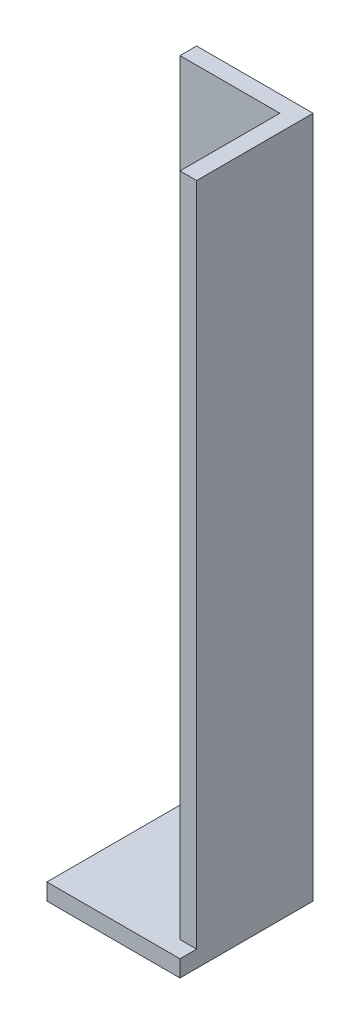
SolidWorks part; units mm, degrees
ref_plane "前视基准面" through (0, 0, 0) normal (0, 0, 1) x (1, 0, 0)
ref_plane "上视基准面" through (0, 0, 0) normal (0, 1, 0) x (1, 0, 0)
ref_plane "右视基准面" through (0, 0, 0) normal (1, 0, 0) x (0, 0, -1)
sketch "草图1" plane through (0, 0, 0) normal (0, 1, 0) x (1, 0, 0)
  line L0 (-38.6765, 43.0123) -> (-38.6765, -56.9877)
  line L1 (-38.6765, -56.9877) -> (61.3235, -56.9877)
  line L2 (61.3235, -56.9877) -> (61.3235, 43.0123)
  line L3 (61.3235, 43.0123) -> (-38.6765, 43.0123)
  dimension "D1" = 100
  dimension "D2" = 100
extrude "凸台-拉伸1" add sketch "草图1" along normal blind 10
sketch "草图2" plane through (0, 10, 0) normal (0, 1, 0) x (1, 0, 0)
  line L4 (61.3235, 43.0123) -> (-38.6765, 43.0123)
  line L5 (-38.6765, 43.0123) -> (-38.6765, -56.9877)
  line L6 (-38.6765, -56.9877) -> (61.3235, -56.9877)
  line L7 (61.3235, -56.9877) -> (61.3235, 43.0123)
  line L8 (61.3235, 43.0123) -> (-38.6765, 43.0123) construction
  line L9 (-38.6765, 43.0123) -> (-38.6765, -56.9877) construction
  line L10 (-38.6765, -56.9877) -> (61.3235, -56.9877) construction
  line L11 (61.3235, -56.9877) -> (61.3235, 43.0123) construction
  line L16 (51.3235, 33.0123) -> (-28.6765, 33.0123)
  line L17 (-28.6765, 33.0123) -> (-28.6765, -46.9877)
  line L18 (-28.6765, -46.9877) -> (51.3235, -46.9877)
  line L19 (51.3235, -46.9877) -> (51.3235, 33.0123)
  line L20 (51.3235, 33.0123) -> (-18.6765, 33.0123)
  line L21 (-28.6765, 33.0123) -> (-28.6765, -46.9877) construction
  line L22 (-28.6765, -46.9877) -> (51.3235, -46.9877) construction
  line L23 (51.3235, -36.9877) -> (51.3235, 33.0123)
  line L24 (-18.6765, 23.0123) -> (-18.6765, 33.0123)
  line L25 (41.3235, -36.9877) -> (51.3235, -36.9877)
  line L28 (41.3235, 23.0123) -> (-18.6765, 23.0123)
  line L29 (-18.6765, 23.0123) -> (-18.6765, -36.9877)
  line L30 (-18.6765, -36.9877) -> (41.3235, -36.9877)
  line L31 (41.3235, -36.9877) -> (41.3235, 23.0123)
  line L32 (41.3235, 23.0123) -> (-18.6765, 23.0123)
  line L33 (-18.6765, 23.0123) -> (-18.6765, -36.9877) construction
  line L34 (-18.6765, -36.9877) -> (41.3235, -36.9877) construction
  line L35 (41.3235, -36.9877) -> (41.3235, 23.0123)
  dimension "D1" = 0
  dimension "D2" = 10
  dimension "D3" = 20
extrude "凸台-拉伸2" add sketch "草图2" along normal blind 400
sketch "草图3" plane through (0, 10, 0) normal (0, 1, 0) x (1, 0, 0)
  line L8 (51.3235, 33.0123) -> (-28.6765, 33.0123)
  line L9 (-28.6765, 33.0123) -> (-28.6765, -46.9877)
  line L10 (-28.6765, -46.9877) -> (51.3235, -46.9877)
  line L11 (51.3235, -46.9877) -> (51.3235, 33.0123)
  line L12 (51.3235, 33.0123) -> (-28.6765, 33.0123)
  line L13 (-28.6765, 33.0123) -> (-28.6765, -46.9877)
  line L14 (-28.6765, -46.9877) -> (51.3235, -46.9877)
  line L15 (51.3235, -46.9877) -> (51.3235, 33.0123)
  dimension "D1" = 10
extrude "切除-拉伸1" cut sketch "草图3" against normal blind 400 flip side to cut
